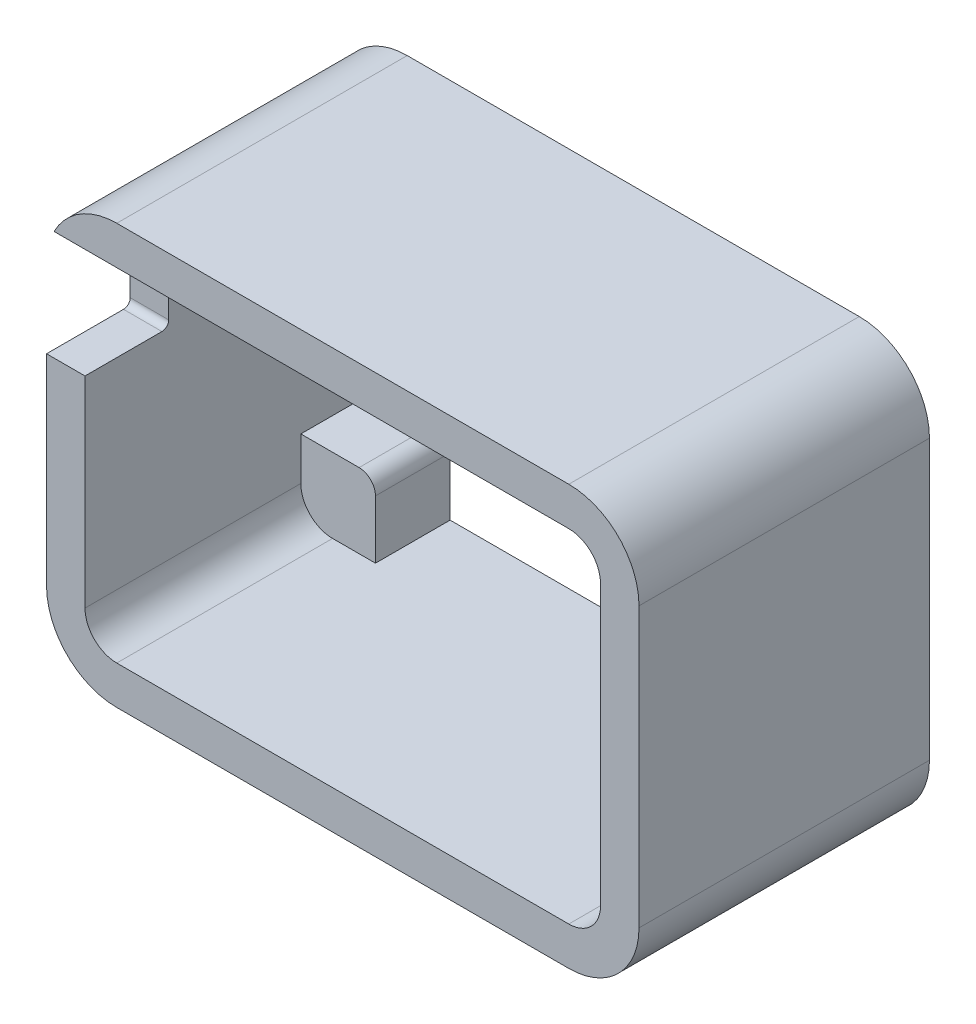
SolidWorks part; units mm, degrees
ref_plane "前视基准面" through (0, 0, 0) normal (0, 0, 1) x (1, 0, 0)
ref_plane "上视基准面" through (0, 0, 0) normal (0, 1, 0) x (1, 0, 0)
ref_plane "右视基准面" through (0, 0, 0) normal (1, 0, 0) x (0, 0, -1)
sketch "草图1" plane through (0, 0, 0) normal (0, 0, 1) x (1, 0, 0)
  line L10 (-13.4, 3.2) -> (-13.4, 7.25)
  line L11 (-3.85, -8.9) -> (3.85, -8.9)
  line L12 (-15.4, 3.2) -> (-15.4, 7.25)
  line L13 (11.75, 10.9) -> (-11.75, 10.9)
  line L14 (15.4, -7.25) -> (15.4, 7.25)
  line L15 (3.85, -10.9) -> (11.75, -10.9)
  line L16 (-3.85, -10.9) -> (3.85, -10.9)
  line L17 (-11.75, -10.9) -> (-3.85, -10.9)
  line L18 (-15.4, 3.2) -> (-15.4, -7.25)
  line L20 (13.4, -7.25) -> (13.4, 7.25)
  line L21 (11.75, 8.9) -> (-16.9, 8.9)
  line L22 (-16.9, 8.9) -> (-16.9, 3.2)
  line L23 (-16.9, 3.2) -> (-13.4, 3.2)
  line L24 (-13.4, 3.2) -> (-13.4, -7.25)
  line L25 (-11.75, -8.9) -> (-3.85, -8.9)
  line L26 (-3.85, -8.9) -> (-3.85, -7.9)
  line L27 (-3.85, -7.9) -> (3.85, -7.9)
  line L28 (3.85, -7.9) -> (3.85, -8.9)
  line L29 (3.85, -8.9) -> (11.75, -8.9)
  line L30 (13.4, -7.25) -> (13.4, 7.25)
  line L31 (11.75, 8.9) -> (-11.75, 8.9)
  line L34 (-13.4, 3.2) -> (-13.4, -7.25)
  line L35 (-11.75, -8.9) -> (-3.85, -8.9)
  line L39 (3.85, -8.9) -> (11.75, -8.9)
  arc A6 (13.4, 7.25) -> (11.75, 8.9) centre (11.75, 7.25) ccw
  arc A7 (-13.4, -7.25) -> (-11.75, -8.9) centre (-11.75, -7.25) ccw
  arc A8 (11.75, -8.9) -> (13.4, -7.25) centre (11.75, -7.25) ccw
  arc A9 (13.4, 7.25) -> (11.75, 8.9) centre (11.75, 7.25) ccw
  arc A10 (-13.4, -7.25) -> (-11.75, -8.9) centre (-11.75, -7.25) ccw
  arc A11 (11.75, -8.9) -> (13.4, -7.25) centre (11.75, -7.25) ccw
  arc A13 (-11.75, 10.9) -> (-15.4, 7.25) centre (-11.75, 7.25) ccw
  arc A14 (15.4, 7.25) -> (11.75, 10.9) centre (11.75, 7.25) ccw
  arc A15 (-11.75, 8.9) -> (-13.4, 7.25) centre (-11.75, 7.25) ccw
  arc A16 (11.75, -10.9) -> (15.4, -7.25) centre (11.75, -7.25) ccw
  arc A17 (-15.4, -7.25) -> (-11.75, -10.9) centre (-11.75, -7.25) ccw
  dimension "D1" = 0.15
  dimension "D2" = 2
extrude "凸台-拉伸1" add sketch "草图1" against normal up to surface (15.1 mm away)
sketch "草图2" plane through (0, 0, -15.1) normal (0, 0, -1) x (-1, 0, 0)
  line L6 (-13.4, -7.25) -> (-13.4, 7.25) construction
  line L7 (-11.75, 8.9) -> (11.75, 8.9) construction
  line L8 (-13.25, 6.82) -> (-11.67, 6.82)
  line L9 (-11.32, 7.17) -> (-11.32, 8.75)
  line L10 (-13.4, 6.82) -> (-11.67, 6.82)
  line L11 (-11.32, 7.17) -> (-11.32, 8.9)
  line L16 (13.4, 7.25) -> (13.4, -7.25) construction
  line L18 (11.67, 6.82) -> (13.25, 6.82)
  line L19 (11.32, 8.75) -> (11.32, 7.17)
  line L20 (11.67, 6.82) -> (13.4, 6.82)
  line L21 (11.32, 8.9) -> (11.32, 7.17)
  line L25 (-9.52, -8.75) -> (-9.52, -5.87)
  line L26 (-10.37, -5.02) -> (-13.25, -5.02)
  line L27 (-9.52, -8.9) -> (-9.52, -5.87)
  line L28 (-10.37, -5.02) -> (-13.4, -5.02)
  line L29 (11.75, -8.9) -> (-11.75, -8.9) construction
  line L31 (9.52, -5.87) -> (9.52, -8.75)
  line L32 (13.25, -5.02) -> (10.37, -5.02)
  line L33 (9.52, -5.87) -> (9.52, -8.9)
  line L34 (13.4, -5.02) -> (10.37, -5.02)
  arc A4 (-11.67, 6.82) -> (-11.32, 7.17) centre (-11.67, 7.17) ccw
  arc A5 (-11.67, 6.82) -> (-11.32, 7.17) centre (-11.67, 7.17) ccw
  arc A8 (11.32, 7.17) -> (11.67, 6.82) centre (11.67, 7.17) ccw
  arc A9 (11.32, 7.17) -> (11.67, 6.82) centre (11.67, 7.17) ccw
  arc A11 (-9.52, -5.87) -> (-10.37, -5.02) centre (-10.37, -5.87) ccw
  arc A12 (-9.52, -5.87) -> (-10.37, -5.02) centre (-10.37, -5.87) ccw
  arc A14 (10.37, -5.02) -> (9.52, -5.87) centre (10.37, -5.87) ccw
  arc A15 (10.37, -5.02) -> (9.52, -5.87) centre (10.37, -5.87) ccw
  line M12 (11.75, -8.9) -> (-11.75, -8.9)
  arc M13 (-11.75, -8.9) -> (-13.4, -7.25) centre (-11.75, -7.25) cw
  line M14 (-13.4, -7.25) -> (-13.4, 7.25)
  arc M15 (-13.4, 7.25) -> (-11.75, 8.9) centre (-11.75, 7.25) cw
  line M16 (-11.75, 8.9) -> (11.75, 8.9)
  arc M17 (11.75, 8.9) -> (13.4, 7.25) centre (11.75, 7.25) cw
  line M18 (13.4, 7.25) -> (13.4, -7.25)
  arc M19 (13.4, -7.25) -> (11.75, -8.9) centre (11.75, -7.25) cw
  dimension "D1" = 0.15
  dimension "D2" = 0.15
  dimension "D3" = 0.15
  dimension "D4" = 0.15
extrude "凸台-拉伸2" add sketch "草图2" against normal up to surface (3.88 mm away) contours L10 A5 L11 M16 M15 M14 | L27 A12 L28 M14 M13 M12 | L34 A15 L33 M12 M19 M18 | L21 A9 L20 M18 M17 M16
sketch "草图3" plane through (-15.4, 0, 0) normal (-1, 0, 0) x (0, 0, 1)
  line L8 (0.15, 8.9) -> (-4, 8.9)
  line L9 (-4.35, 8.55) -> (-4.35, 3.55)
  line L10 (-4, 3.2) -> (0.15, 3.2)
  line L11 (0.15, 3.2) -> (0.15, 8.9)
  line L12 (0.15, 8.9) -> (-4, 8.9)
  line L13 (-4.35, 8.55) -> (-4.35, 3.55)
  line L14 (-4, 3.2) -> (0.15, 3.2)
  line L15 (0.15, 3.2) -> (0.15, 8.9)
  arc A4 (-4, 8.9) -> (-4.35, 8.55) centre (-4, 8.55) ccw
  arc A5 (-4.35, 3.55) -> (-4, 3.2) centre (-4, 3.55) ccw
  arc A6 (-4, 8.9) -> (-4.35, 8.55) centre (-4, 8.55) ccw
  arc A7 (-4.35, 3.55) -> (-4, 3.2) centre (-4, 3.55) ccw
  dimension "D1" = 0.15
extrude "切除-拉伸1" cut sketch "草图3" against normal up to next
